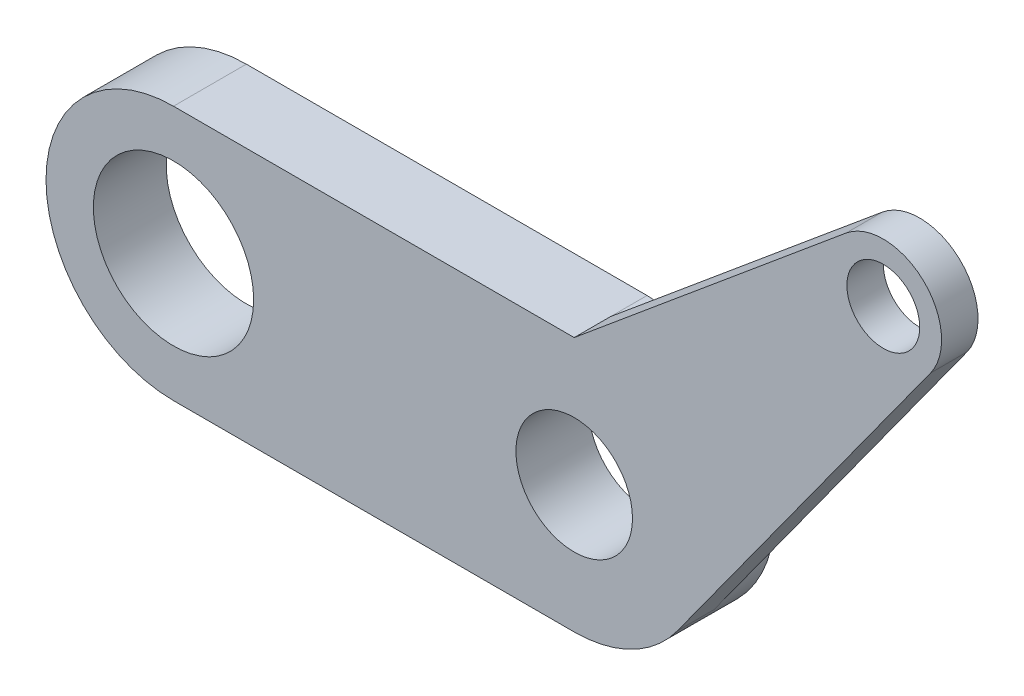
SolidWorks part; units mm, degrees
ref_plane "Спереди" through (0, 0, 0) normal (0, 0, 1) x (1, 0, 0)
ref_plane "Сверху" through (0, 0, 0) normal (0, 1, 0) x (1, 0, 0)
ref_plane "Справа" through (0, 0, 0) normal (1, 0, 0) x (0, 0, -1)
sketch "Эскиз1" plane through (0, 0, 0) normal (0, 0, 1) x (1, 0, 0)
  line L0 (-27.5, 0) -> (27.5, 0) construction
  line L1 (-27.5, 17.5) -> (27.5, 17.5)
  line L2 (-27.5, -17.5) -> (27.5, -17.5)
  arc A0 (-27.5, 17.5) -> (-27.5, -17.5) centre (-27.5, 0) ccw
  arc A1 (27.5, -17.5) -> (27.5, 17.5) centre (27.5, 0) ccw
  circle A2 centre (-27.5, 0) radius 11
  circle A3 centre (27.5, 0) radius 8
  point P2 (0, 0)
  dimension "D3" = 22
  dimension "D4" = 16
  dimension "D1" = 35
  dimension "D2" = 55
extrude "Бобышка-Вытянуть1" add sketch "Эскиз1" along normal blind 10
sketch "Эскиз2" plane through (0, 0, 10) normal (0, 0, 1) x (1, 0, 0)
  line L0 (27.5, 0) -> (69.9264, 42.4264) construction
  line L1 (41.6775, -10.259) -> (76.4076, 37.7366)
  line L2 (27.5, 17.5) -> (64.8064, 48.5734)
  line L3 (27.5, 0) -> (27.5, 48.6308) construction
  circle A0 centre (69.9264, 42.4264) radius 5
  circle A1 centre (69.9264, 42.4264) radius 8
  arc A2 (27.5, -17.5) -> (27.5, 17.5) centre (27.5, 0) ccw construction
  arc A3 (41.6775, -10.259) -> (27.5, 17.5) centre (27.5, 0) ccw
  arc M4 (27.5, -17.5) -> (27.5, 17.5) centre (27.5, 0) ccw
  dimension "D1" = 10
  dimension "D2" = 16
  dimension "D3" = 45
  dimension "D4" = 60
extrude "Бобышка-Вытянуть2" add sketch "Эскиз2" against normal blind 5 contours A1 L2 L1 M4 | A1 A0
